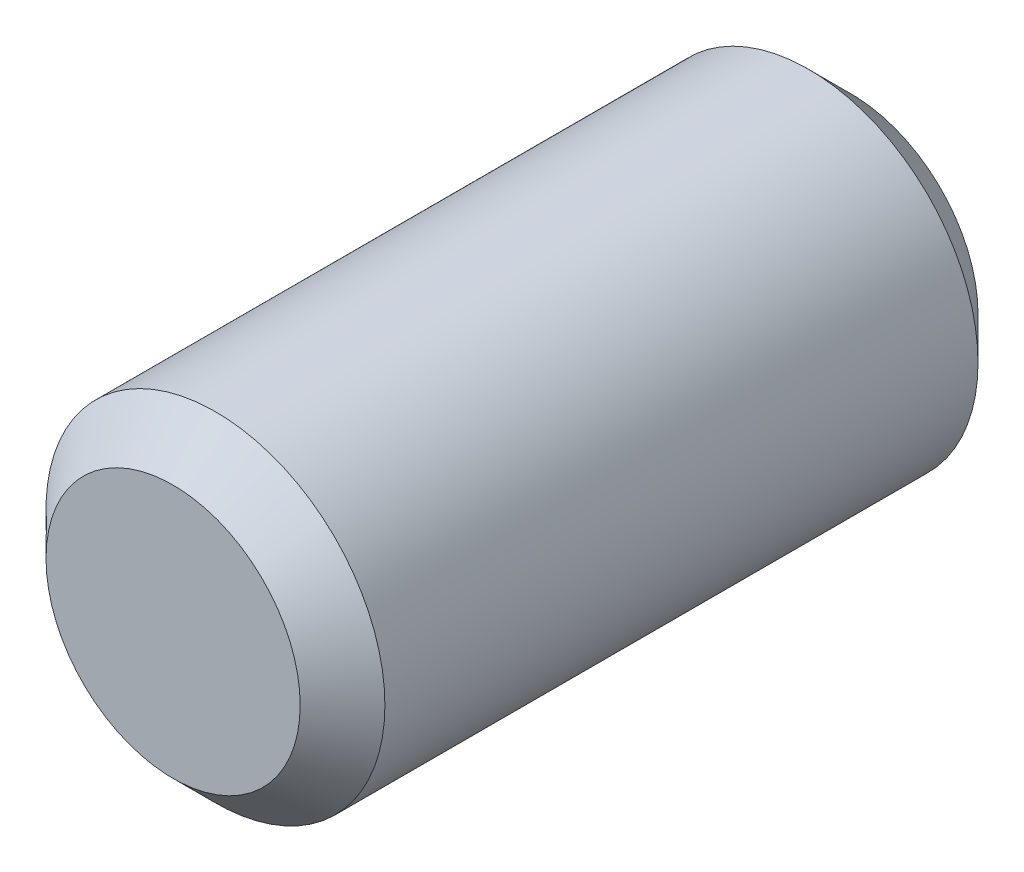
SolidWorks part; units mm, degrees
material "AISI 1020"
ref_plane "Face" through (0, 0, 0) normal (0, 0, 1) x (1, 0, 0)
ref_plane "Dessus" through (0, 0, 0) normal (0, 1, 0) x (1, 0, 0)
ref_plane "Droite" through (0, 0, 0) normal (1, 0, 0) x (0, 0, -1)
sketch "Esquisse1" plane through (0, 0, 0) normal (0, 0, 1) x (1, 0, 0)
  circle A0 centre (0, 0) radius 2
extrude "Boss.-Extru.1" add sketch "Esquisse1" along normal mid plane 8
chamfer "Chanfrein1" distance 0.5 angle 45 2 edges at (2, 0, -4) (2, 0, 4)
